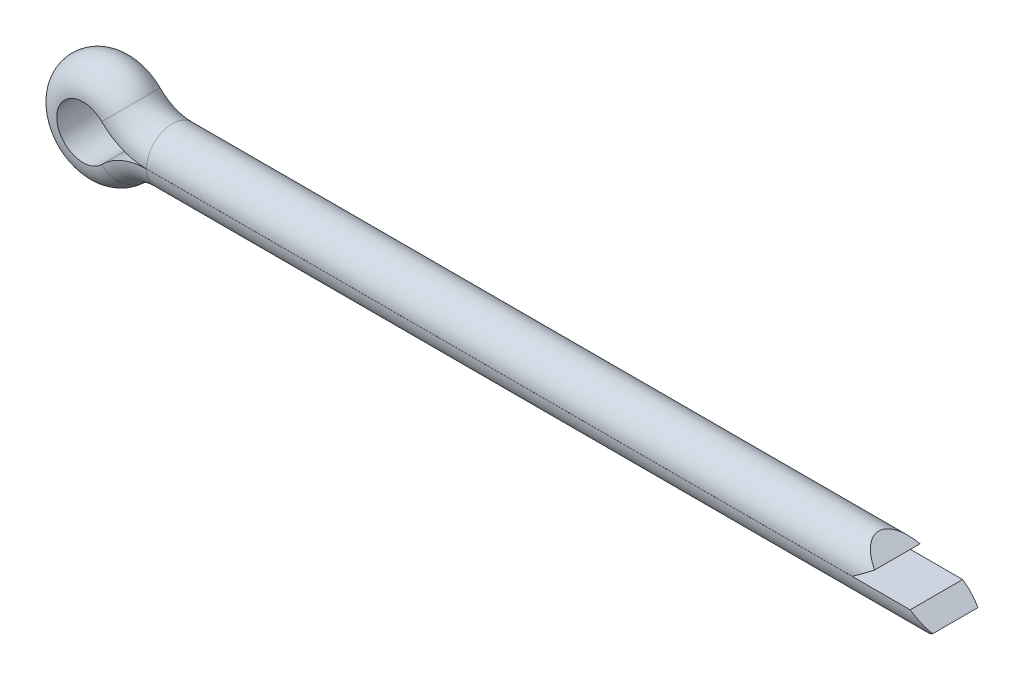
SolidWorks part; units mm, degrees
ref_plane "Front" through (0, 0, 0) normal (0, 0, 1) x (1, 0, 0)
ref_plane "Top" through (0, 0, 0) normal (0, 1, 0) x (1, 0, 0)
ref_plane "Right" through (0, 0, 0) normal (1, 0, 0) x (0, 0, -1)
sketch "PathSke" plane through (0, 0, 0) normal (0, 0, 1) x (1, 0, 0)
  line L0 (40, 1.45) -> (0, 1.45)
  line L1 (0, -1.45) -> (43.2, -1.45)
  line L2 (0, 0) -> (49.7718, 0) construction
  line L3 (0, 0) -> (0, 16.5256) construction
  line L4 (-6.4, 0) -> (-6.4, 14.2137) construction
  arc A0 (0, 1.45) -> (-1.4491, 2.0504) centre (0, 3.4991) cw
  arc A1 (-1.4491, 2.0504) -> (-1.4491, -2.0504) centre (-3.5, 0) ccw
  arc A2 (-1.4491, -2.0504) -> (0, -1.45) centre (0, -3.4991) cw
  dimension "Diameter" = 2.9
  dimension "Head_dia" = 5.8
  dimension "Head_ht" = 6.4
  dimension "Length" = 40
  dimension "Tip_offset" = 3.2
ref_plane "SectionPlane" through (40, 0, 0) normal (1, 0, 0) x (0, 0, -1)
sketch "SectionSke" plane through (40, 0, 0) normal (1, 0, 0) x (0, 0, -1)
  line L1 (-1.45, 0.002) -> (1.45, 0.002)
  arc A0 (1.45, 0.002) -> (-1.45, 0.002) centre (0, 0) ccw
  dimension "Diameter" = 2.9
  dimension "D1" = 0.002
sweep "Body" add profiles "SectionSke" path "PathSke"
sketch "ConeCutSke" plane through (0, 0, 0) normal (0, 0, 1) x (1, 0, 0)
  line L0 (0, 0) -> (0, 16.2682) construction
  line L1 (0, 0) -> (75.9079, 0) construction
  line L2 (0, 0) -> (43.2, 0) construction
  line L3 (40, 0.726) -> (38.9603, 1.46)
  line L4 (40, 0.002) -> (40, 1.45) construction
  line L6 (40, 0.726) -> (38.9547, 0)
  line L7 (43.2, -0.726) -> (42.1547, 0)
  line L8 (43.2, -1.45) -> (43.2, -0.002) construction
  line L9 (43.2, -0.726) -> (42.1603, -1.46)
  line L10 (42.1547, 0) -> (38.9547, 0)
  line L11 (38.9603, 1.46) -> (43.21, 1.46)
  line L12 (43.21, 1.46) -> (43.21, -1.46)
  line L13 (43.21, -1.46) -> (42.1603, -1.46)
  line L14 (40, 1.45) -> (0, 1.45) construction
  dimension "D1" = 0.01
  dimension "D2" = 0.01
  dimension "D3" = 70
  dimension "D4" = 70
extrude "ConeCut" cut sketch "ConeCutSke" against normal through all and the other way through all
equation "' \"Diameter@PathSke\" = 9.5"
equation "' \"Head_dia@PathSke\" = 19"
equation "' \"Head_ht@PathSke\" = 20"
equation "' \"Tip_offset@PathSke\" = 6.3"
equation "' \"Length@PathSke\" = 45"
equation "' \"Diameter@PathSke\" = 1"
equation "' \"Head_dia@PathSke\" = 2"
equation "' \"Head_ht@PathSke\" = 3"
equation "' \"Tip_offset@PathSke\" = 2.5"
equation "' \"Length@PathSke\" = 8"
equation "' \"Diameter@PathSke\" = 0.5"
equation "' \"Head_dia@PathSke\" = 1"
equation "' \"Head_ht@PathSke\" = 2"
equation "' \"Tip_offset@PathSke\" = 1.6"
equation "' \"Length@PathSke\" = 4"
equation "\"Diameter@SectionSke\" = \"Diameter@PathSke\""
equation "\"Length@SectionPlane\" = \"Length@PathSke\""
